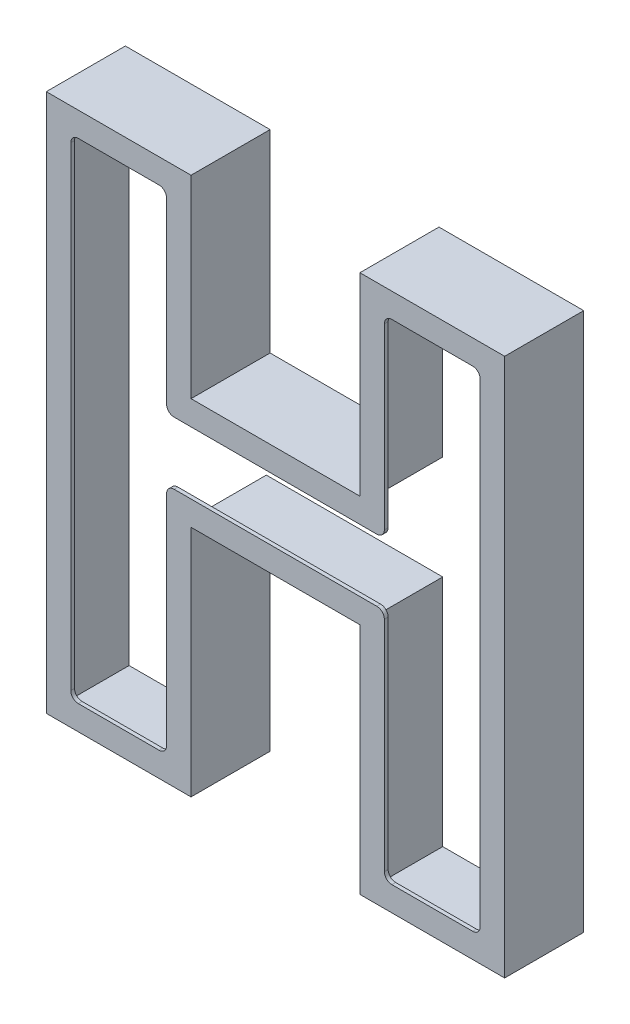
SolidWorks part; units mm, degrees
ref_plane "Front Plane" through (0, 0, 0) normal (0, 0, 1) x (1, 0, 0)
ref_plane "Top Plane" through (0, 0, 0) normal (0, 1, 0) x (1, 0, 0)
ref_plane "Right Plane" through (0, 0, 0) normal (1, 0, 0) x (0, 0, -1)
sketch "Sketch1" plane through (0, 0, 0) normal (0, 0, 1) x (1, 0, 0)
  line L90 (3401.8434, -1645.5826) -> (3440.2864, -1645.5826)
  line L91 (3401.8434, -1583.5573) -> (3401.8434, -1645.5826)
  line L92 (3356.9953, -1583.5573) -> (3401.8434, -1583.5573)
  line L93 (3356.9953, -1645.5826) -> (3356.9953, -1583.5573)
  line L94 (3318.5522, -1645.5826) -> (3356.9953, -1645.5826)
  line L95 (3318.5522, -1502.5826) -> (3318.5522, -1645.5826)
  line L96 (3356.9953, -1502.5826) -> (3318.5522, -1502.5826)
  line L97 (3356.9953, -1553.975) -> (3356.9953, -1502.5826)
  line L98 (3401.8434, -1553.975) -> (3356.9953, -1553.975)
  line L99 (3401.8434, -1502.5826) -> (3401.8434, -1553.975)
  line L100 (3440.2864, -1502.5826) -> (3401.8434, -1502.5826)
  line L101 (3440.2864, -1645.5826) -> (3440.2864, -1502.5826)
  line L102 (3401.8434, -1645.5826) -> (3440.2864, -1645.5826)
  line L103 (3401.8434, -1583.5573) -> (3401.8434, -1645.5826)
  line L104 (3356.9953, -1583.5573) -> (3401.8434, -1583.5573)
  line L105 (3356.9953, -1645.5826) -> (3356.9953, -1583.5573)
  line L106 (3318.5522, -1645.5826) -> (3356.9953, -1645.5826)
  line L107 (3318.5522, -1502.5826) -> (3318.5522, -1645.5826)
  line L108 (3356.9953, -1502.5826) -> (3318.5522, -1502.5826)
  line L109 (3356.9953, -1553.975) -> (3356.9953, -1502.5826)
  line L110 (3401.8434, -1553.975) -> (3356.9953, -1553.975)
  line L111 (3401.8434, -1502.5826) -> (3401.8434, -1553.975)
  line L112 (3440.2864, -1502.5826) -> (3401.8434, -1502.5826)
  line L113 (3440.2864, -1645.5826) -> (3440.2864, -1502.5826)
  dimension "D1" = 1.5
extrude "Boss-Extrude1" add sketch "Sketch1" along normal blind 1 and the other way blind 20
sketch "Sketch2" plane through (0, 0, 1) normal (0, 0, 1) x (1, 0, 0)
  line L24 (3408.3434, -1577.0573) -> (3408.3434, -1639.0826)
  line L25 (3408.3434, -1639.0826) -> (3433.7864, -1639.0826)
  line L26 (3433.7864, -1639.0826) -> (3433.7864, -1509.0826)
  line L27 (3433.7864, -1509.0826) -> (3408.3434, -1509.0826)
  line L28 (3408.3434, -1509.0826) -> (3408.3434, -1560.475)
  line L29 (3408.3434, -1560.475) -> (3350.4953, -1560.475)
  line L30 (3350.4953, -1560.475) -> (3350.4953, -1509.0826)
  line L31 (3350.4953, -1509.0826) -> (3325.0522, -1509.0826)
  line L32 (3325.0522, -1509.0826) -> (3325.0522, -1639.0826)
  line L33 (3325.0522, -1639.0826) -> (3350.4953, -1639.0826)
  line L34 (3350.4953, -1639.0826) -> (3350.4953, -1577.0573)
  line L35 (3350.4953, -1577.0573) -> (3408.3434, -1577.0573)
  line L36 (3408.3434, -1577.0573) -> (3408.3434, -1639.0826)
  line L37 (3408.3434, -1639.0826) -> (3433.7864, -1639.0826)
  line L38 (3433.7864, -1639.0826) -> (3433.7864, -1509.0826)
  line L39 (3433.7864, -1509.0826) -> (3408.3434, -1509.0826)
  line L40 (3408.3434, -1509.0826) -> (3408.3434, -1560.475)
  line L41 (3408.3434, -1560.475) -> (3350.4953, -1560.475)
  line L42 (3350.4953, -1560.475) -> (3350.4953, -1509.0826)
  line L43 (3350.4953, -1509.0826) -> (3325.0522, -1509.0826)
  line L44 (3325.0522, -1509.0826) -> (3325.0522, -1639.0826)
  line L45 (3325.0522, -1639.0826) -> (3350.4953, -1639.0826)
  line L46 (3350.4953, -1639.0826) -> (3350.4953, -1577.0573)
  line L47 (3350.4953, -1577.0573) -> (3408.3434, -1577.0573)
  dimension "D1" = 6.5
extrude "Cut-Extrude1" cut sketch "Sketch2" against normal through all
sketch "Sketch3" plane through (0, 0, -20) normal (0, 0, -1) x (-1, 0, 0)
  line L24 (-3402.8434, -1644.5826) -> (-3402.8434, -1582.5573)
  line L25 (-3402.8434, -1582.5573) -> (-3355.9953, -1582.5573)
  line L26 (-3355.9953, -1582.5573) -> (-3355.9953, -1644.5826)
  line L27 (-3355.9953, -1644.5826) -> (-3319.5522, -1644.5826)
  line L28 (-3319.5522, -1644.5826) -> (-3319.5522, -1503.5826)
  line L29 (-3319.5522, -1503.5826) -> (-3355.9953, -1503.5826)
  line L30 (-3355.9953, -1503.5826) -> (-3355.9953, -1554.975)
  line L31 (-3355.9953, -1554.975) -> (-3402.8434, -1554.975)
  line L32 (-3402.8434, -1554.975) -> (-3402.8434, -1503.5826)
  line L33 (-3402.8434, -1503.5826) -> (-3439.2864, -1503.5826)
  line L34 (-3439.2864, -1503.5826) -> (-3439.2864, -1644.5826)
  line L35 (-3439.2864, -1644.5826) -> (-3402.8434, -1644.5826)
  line L36 (-3402.8434, -1644.5826) -> (-3402.8434, -1582.5573)
  line L37 (-3402.8434, -1582.5573) -> (-3355.9953, -1582.5573)
  line L38 (-3355.9953, -1582.5573) -> (-3355.9953, -1644.5826)
  line L39 (-3355.9953, -1644.5826) -> (-3319.5522, -1644.5826)
  line L40 (-3319.5522, -1644.5826) -> (-3319.5522, -1503.5826)
  line L41 (-3319.5522, -1503.5826) -> (-3355.9953, -1503.5826)
  line L42 (-3355.9953, -1503.5826) -> (-3355.9953, -1554.975)
  line L43 (-3355.9953, -1554.975) -> (-3402.8434, -1554.975)
  line L44 (-3402.8434, -1554.975) -> (-3402.8434, -1503.5826)
  line L45 (-3402.8434, -1503.5826) -> (-3439.2864, -1503.5826)
  line L46 (-3439.2864, -1503.5826) -> (-3439.2864, -1644.5826)
  line L47 (-3439.2864, -1644.5826) -> (-3402.8434, -1644.5826)
  dimension "D1" = 1
extrude "Cut-Extrude2" cut sketch "Sketch3" against normal blind 20
fillet "Fillet1" radius 2 12 edges at (3325.0522, -1639.0826, 0.5) (3350.4953, -1639.0826, 0.5) (3350.4953, -1577.0573, 0.5) (3433.7864, -1639.0826, 0.5) (3408.3434, -1639.0826, 0.5) (3408.3434, -1577.0573, 0.5) (3325.0522, -1509.0826, 0.5) (3350.4953, -1509.0826, 0.5) (3350.4953, -1560.475, 0.5) (3408.3434, -1509.0826, 0.5) (3408.3434, -1560.475, 0.5) (3433.7864, -1509.0826, 0.5)
